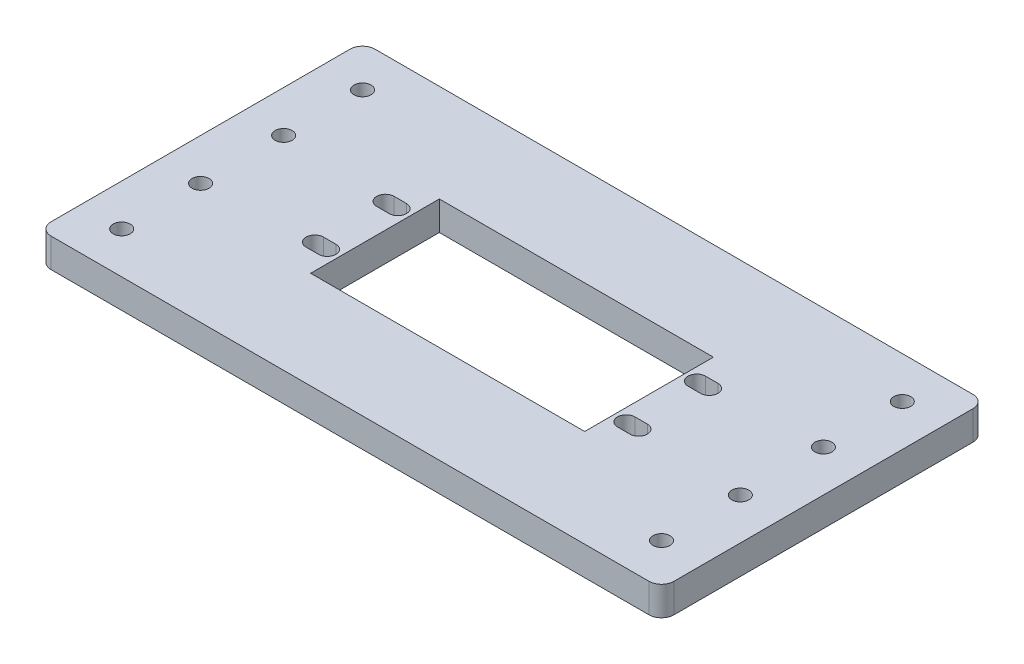
SolidWorks part; units mm, degrees
ref_plane "Front Plane" through (0, 0, 0) normal (0, 0, 1) x (1, 0, 0)
ref_plane "Top Plane" through (0, 0, 0) normal (0, 1, 0) x (1, 0, 0)
ref_plane "Right Plane" through (0, 0, 0) normal (1, 0, 0) x (0, 0, -1)
sketch "Sketch2" plane through (0, 0, 0) normal (0, 1, 0) x (1, 0, 0)
  line L0 (-75, 0) -> (75, 0) construction
  line L1 (-75, 39) -> (75, 39)
  line L2 (-75, 39) -> (-75, -39)
  line L3 (-75, -39) -> (75, -39)
  line L4 (75, 39) -> (75, -39)
  line L5 (-75, 39) -> (75, -39) construction
  line L6 (-75, -39) -> (75, 39) construction
  line L7 (-37.5, 8.5) -> (-37.5, -8.5)
  line L8 (-33, 15.5) -> (33, 15.5)
  line L9 (-33, 15.5) -> (-33, -15.5)
  line L10 (-33, -15.5) -> (33, -15.5)
  line L11 (33, 15.5) -> (33, -15.5)
  line L12 (-33, 15.5) -> (33, -15.5) construction
  line L13 (-33, -15.5) -> (33, 15.5) construction
  line L14 (0, 15.5) -> (0, -15.5) construction
  line L15 (-39, 8.5) -> (-36, 8.5) construction
  line L16 (-39, 10.6) -> (-36, 10.6)
  line L17 (-39, 6.4) -> (-36, 6.4)
  line L18 (-39, -8.5) -> (-36, -8.5) construction
  line L19 (-39, -10.6) -> (-36, -10.6)
  line L20 (-39, -6.4) -> (-36, -6.4)
  line L21 (39, -8.5) -> (36, -8.5) construction
  line L22 (39, -10.6) -> (36, -10.6)
  line L23 (39, -6.4) -> (36, -6.4)
  line L24 (39, 8.5) -> (36, 8.5) construction
  line L25 (39, 10.6) -> (36, 10.6)
  line L26 (39, 6.4) -> (36, 6.4)
  arc A4 (-39, 10.6) -> (-39, 6.4) centre (-39, 8.5) ccw
  arc A5 (-36, 6.4) -> (-36, 10.6) centre (-36, 8.5) ccw
  arc A6 (-39, -10.6) -> (-39, -6.4) centre (-39, -8.5) cw
  arc A7 (-36, -6.4) -> (-36, -10.6) centre (-36, -8.5) cw
  arc A8 (39, -10.6) -> (39, -6.4) centre (39, -8.5) ccw
  arc A9 (36, -6.4) -> (36, -10.6) centre (36, -8.5) ccw
  arc A10 (39, 10.6) -> (39, 6.4) centre (39, 8.5) cw
  arc A11 (36, 6.4) -> (36, 10.6) centre (36, 8.5) cw
  point P0 (0, 0)
  point P6 (-20, 0)
  point P9 (0, 0)
  point P17 (-37.5, 0)
  point P22 (-37.5, -8.5)
  point P26 (-37.5, 8.5)
  point P35 (37.5, -8.5)
  point P42 (37.5, 8.5)
  dimension "D10" = 3
  dimension "D12" = 2.1
  dimension "D1" = 78
  dimension "D2" = 150
  dimension "D3" = 20
  dimension "D4" = 39
  dimension "D5" = 66
  dimension "D6" = 31
  dimension "D7" = 13
  dimension "D8" = 17
  dimension "D9" = 37.5
extrude "Boss-Extrude1" add sketch "Sketch2" along normal blind 7
sketch "Sketch3" plane through (0, 7, 0) normal (0, 1, 0) x (1, 0, 0)
  line L0 (75, 39) -> (75, -39) construction
  line L1 (-65, 29) -> (65, 29) construction
  line L2 (-65, 29) -> (-65, -29) construction
  line L3 (-65, -29) -> (65, -29) construction
  line L4 (65, 29) -> (65, -29) construction
  line L5 (-65, 29) -> (65, -29) construction
  line L6 (-65, -29) -> (65, 29) construction
  line L7 (-75, 39) -> (75, 39) construction
  line L8 (-65, 0) -> (65, 0) construction
  line L9 (0, 29) -> (0, -29) construction
  circle A0 centre (-65, 10) radius 2.05
  circle A1 centre (-65, 29) radius 2.05
  circle A2 centre (-65, -10) radius 2.05
  circle A3 centre (-65, -29) radius 2.05
  circle A4 centre (65, -29) radius 2.05
  circle A5 centre (65, -10) radius 2.05
  circle A6 centre (65, 10) radius 2.05
  circle A7 centre (65, 29) radius 2.05
  point P0 (0, 0)
  dimension "D3" = 4.1
  dimension "D5" = 4.1
  dimension "D1" = 10
  dimension "D2" = 10
  dimension "D4" = 10
fillet "Fillet1" radius 3 4 edges at (-75, 3.5, 39) (75, 3.5, 39) (75, 3.5, -39) (-75, 3.5, -39)
extrude "Cut-Extrude1" cut sketch "Sketch3" against normal blind 10
